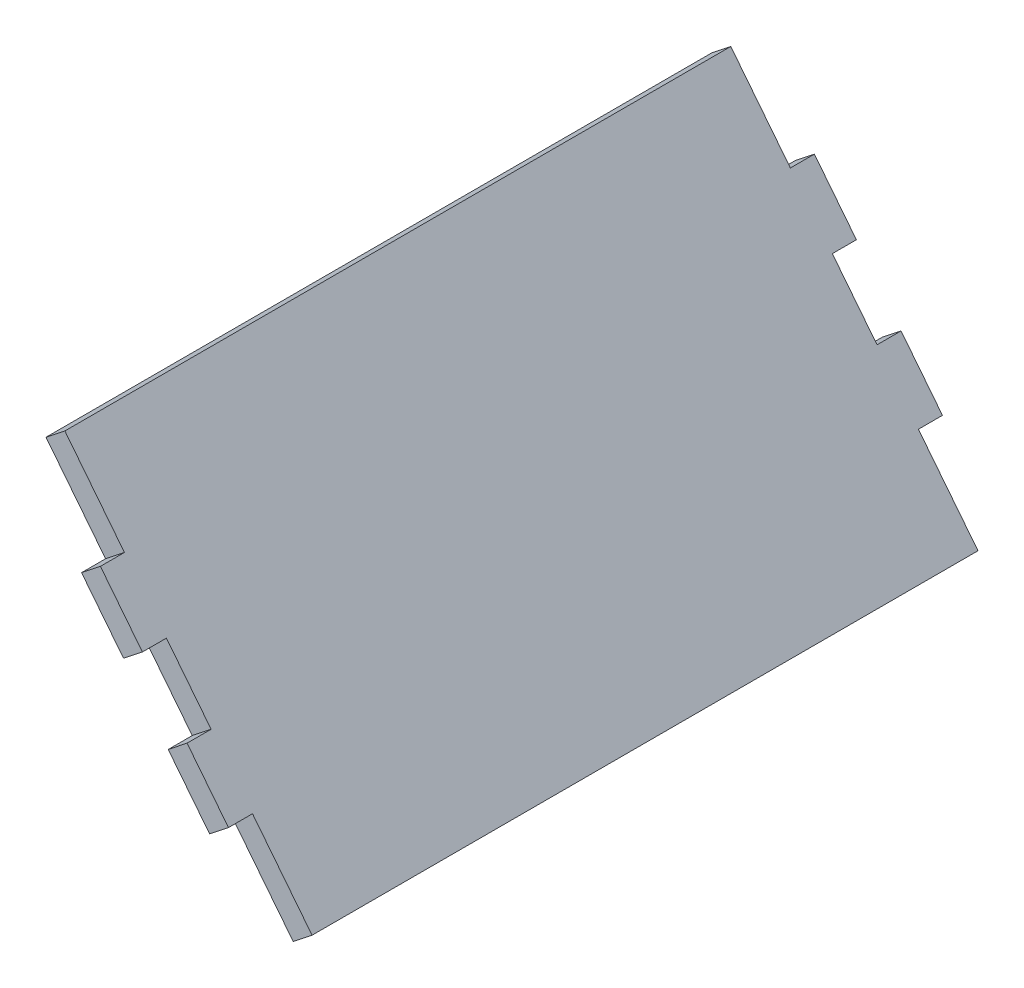
SolidWorks part; units mm, degrees
ref_plane "Front Plane" through (0, 0, 0) normal (0, 0, 1) x (1, 0, 0)
ref_plane "Top Plane" through (0, 0, 0) normal (0, 1, 0) x (1, 0, 0)
ref_plane "Right Plane" through (0, 0, 0) normal (1, 0, 0) x (0, 0, -1)
sketch "Sketch1" plane through (0, 0, 0) normal (0, 0, 1) x (1, 0, 0)
  line L0 (-57.5598, 25.9505) -> (-90.218, 67.3176)
  line L1 (-90.218, 67.3176) -> (-92.71, 65.3502)
  line L2 (-92.71, 65.3502) -> (-60.0518, 23.9831)
  line L3 (-60.0518, 23.9831) -> (-57.5598, 25.9505)
  line L4 (-44.4278, 16.9374) -> (-63.4778, 16.9374) construction
  dimension "D1" = 128.29
  dimension "D2" = 7.0457
  dimension "D3" = 3.175
extrude "Boss-Extrude1" add sketch "Sketch1" against normal up to vertex (94.3225 mm away) contours L0 L1 L2 L3
sketch "Sketch2" plane through (-22.8382, -18.0301, 0) normal (0.7849, 0.6196, 0) x (0, 0, -1)
  line L0 (91.1475, 251.0874) -> (91.1475, 40.8233) construction
  line L1 (94.3225, 108.7395) -> (91.1475, 108.7395)
  line L2 (94.3225, 108.7395) -> (94.3225, 96.0395)
  line L3 (94.3225, 96.0395) -> (91.1475, 96.0395)
  line L4 (91.1475, 108.7395) -> (91.1475, 96.0395)
  line L5 (94.3225, 40.8233) -> (94.3225, 251.0874) construction
  line L6 (94.3225, 87.0862) -> (91.1475, 87.0862)
  line L7 (94.3225, 87.0862) -> (94.3225, 77.5612)
  line L8 (94.3225, 77.5612) -> (91.1475, 77.5612)
  line L9 (91.1475, 87.0862) -> (91.1475, 77.5612)
  line L10 (47.1613, 108.7395) -> (47.1613, 98.3874)
  line L11 (94.3225, 56.0347) -> (91.1475, 56.0347)
  line L12 (94.3225, 56.0347) -> (94.3225, 68.7347)
  line L13 (94.3225, 68.7347) -> (91.1475, 68.7347)
  line L14 (91.1475, 56.0347) -> (91.1475, 68.7347)
  line L15 (94.3225, 108.7395) -> (0, 108.7395) construction
  line L16 (0, 56.0347) -> (3.175, 56.0347)
  line L17 (0, 56.0347) -> (0, 68.7347)
  line L18 (3.175, 56.0347) -> (3.175, 68.7347)
  line L19 (0, 68.7347) -> (3.175, 68.7347)
  line L20 (0, 77.5612) -> (3.175, 77.5612)
  line L21 (3.175, 87.0862) -> (3.175, 77.5612)
  line L22 (0, 87.0862) -> (0, 77.5612)
  line L23 (0, 87.0862) -> (3.175, 87.0862)
  line L24 (0, 108.7395) -> (3.175, 108.7395)
  line L25 (0, 108.7395) -> (0, 96.0395)
  line L26 (0, 96.0395) -> (3.175, 96.0395)
  line L27 (3.175, 108.7395) -> (3.175, 96.0395)
  line M14 (0, 108.7395) -> (0, 56.0347)
  line M15 (0, 56.0347) -> (94.3225, 56.0347)
  line M16 (94.3225, 56.0347) -> (94.3225, 108.7395)
  line M17 (94.3225, 108.7395) -> (0, 108.7395)
  dimension "D1" = 12.7
  dimension "D2" = 9.525
  dimension "D3" = 12.7
  dimension "D4" = 8.8265
extrude "Cut-Extrude1" cut sketch "Sketch2" against normal through all contours L4 L3 M17 M16 | L6 L9 L8 M16 | L14 L13 M15 M16 | L27 L26 M17 M14 | L23 L20 L21 M14 | L19 L18 M14 M15
